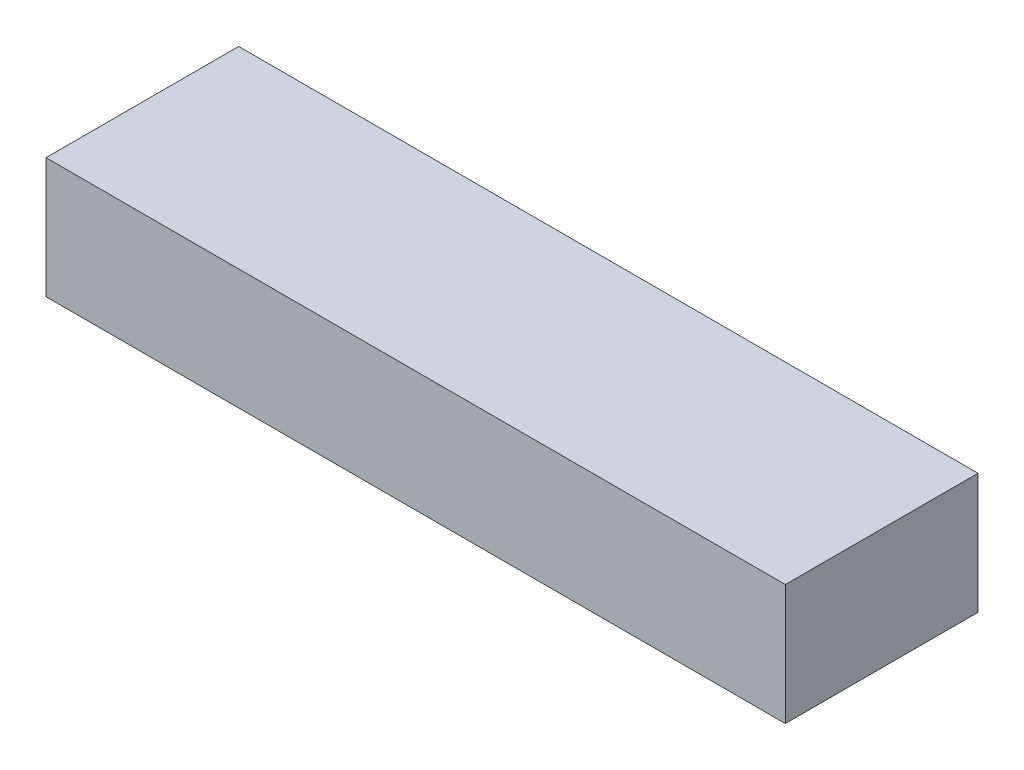
SolidWorks part; units mm, degrees
ref_plane "Front Plane" through (0, 0, 0) normal (0, 0, 1) x (1, 0, 0)
ref_plane "Top Plane" through (0, 0, 0) normal (0, 1, 0) x (1, 0, 0)
ref_plane "Right Plane" through (0, 0, 0) normal (1, 0, 0) x (0, 0, -1)
sketch "Sketch1" plane through (0, 0, 0) normal (0, 1, 0) x (1, 0, 0)
  line L1 (0, 0) -> (116.1796, 0)
  line L2 (0, 0) -> (0, 30.2768)
  line L3 (0, 30.2768) -> (116.1796, 30.2768)
  line L4 (116.1796, 0) -> (116.1796, 30.2768)
  dimension "D1" = 116.1796
  dimension "D2" = 30.2768
extrude "Boss-Extrude1" add sketch "Sketch1" along normal blind 18.923
